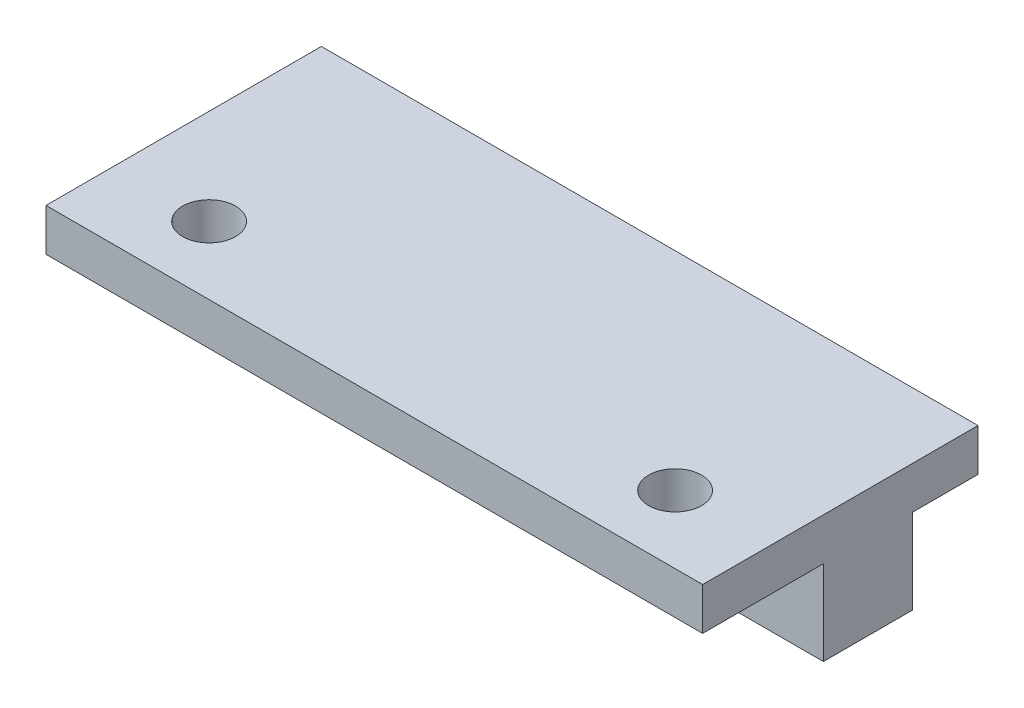
SolidWorks part; units mm, degrees
ref_plane "Front Plane" through (0, 0, 0) normal (0, 0, 1) x (1, 0, 0)
ref_plane "Top Plane" through (0, 0, 0) normal (0, 1, 0) x (1, 0, 0)
ref_plane "Right Plane" through (0, 0, 0) normal (1, 0, 0) x (0, 0, -1)
sketch "Sketch1" plane through (0, 0, 0) normal (0, 1, 0) x (1, 0, 0)
  line L0 (15.5, 0) -> (15.5, 13) construction
  line L1 (0, 0) -> (31, 0)
  line L2 (0, 0) -> (0, 13)
  line L3 (0, 13) -> (31, 13)
  line L4 (31, 0) -> (31, 13)
  circle A0 centre (4.5, 3.2) radius 1.25
  circle A1 centre (26.5, 3.2) radius 1.25
  dimension "D3" = 2.5
  dimension "D4" = 4.5
  dimension "D5" = 3.2
  dimension "D1" = 31
  dimension "D2" = 13
extrude "Boss-Extrude1" add sketch "Sketch1" along normal blind 2
sketch "Sketch2" plane through (0, 0, 0) normal (0, -1, 0) x (1, 0, 0)
  line L0 (31, 0) -> (31, -13) construction
  line L1 (0, -5.7) -> (31, -5.7)
  line L2 (0, -5.7) -> (0, -9.9)
  line L3 (0, -9.9) -> (31, -9.9)
  line L4 (31, -5.7) -> (31, -9.9)
  line L5 (0, -13) -> (0, 0) construction
  line L7 (1.7, -6.7) -> (29.3, -6.7)
  line L8 (1.7, -6.7) -> (1.7, -8.9)
  line L9 (1.7, -8.9) -> (29.3, -8.9)
  line L10 (29.3, -6.7) -> (29.3, -8.9)
  circle A0 centre (4.5, -3.2) radius 1.25 construction
  point P14 (15.5, -6.7)
  point P15 (15.5, -5.7)
  dimension "D2" = 2.5
  dimension "D1" = 4.2
  dimension "D3" = 2.2
  dimension "D5" = 1
  dimension "D6" = 27.6
extrude "Boss-Extrude2" add sketch "Sketch2" along normal blind 4
